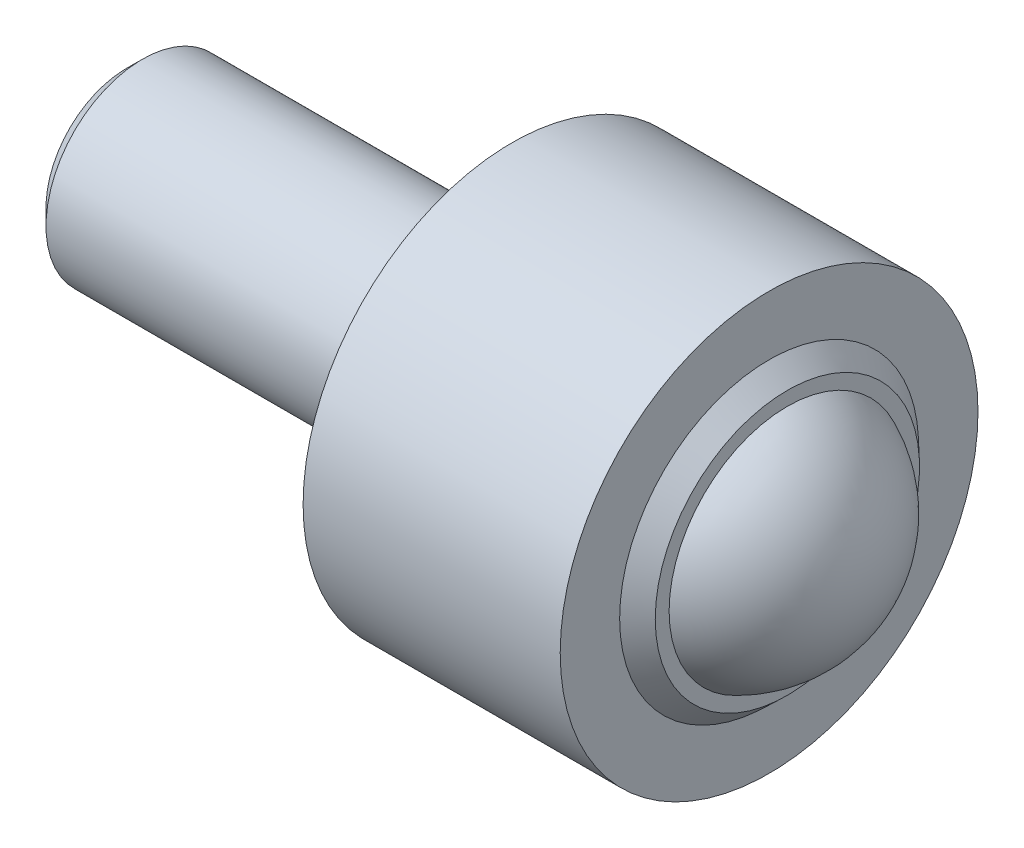
SolidWorks part; units mm, degrees
ref_plane "Front" through (0, 0, 0) normal (0, 0, 1) x (1, 0, 0)
ref_plane "Top" through (0, 0, 0) normal (0, 1, 0) x (1, 0, 0)
ref_plane "Right" through (0, 0, 0) normal (1, 0, 0) x (0, 0, -1)
sketch "草图1" plane through (0, 0, 0) normal (1, 0, 0) x (0, 0, -1)
  circle A0 centre (0, 0) radius 3
  dimension "D1" = 6
extrude "凸台-拉伸1" add sketch "草图1" along normal blind 12
cosmetic thread "装饰螺纹线1" parameters "D1"=5, "D2"=4.917
sketch "草图2" plane through (12, 0, 0) normal (1, 0, 0) x (0, 0, -1)
  circle A0 centre (0, 0) radius 6.5
  dimension "D1" = 13
extrude "凸台-拉伸2" add sketch "草图2" along normal blind 8
sketch "草图3" plane through (0, 0, 0) normal (0, 1, 0) x (1, 0, 0)
  line L0 (0, 0) -> (29.5776, 0) construction
  line L1 (20, -6.5) -> (20, 6.5) construction
  line L2 (15, 0) -> (23, 0)
  line L3 (20, 4.6509) -> (20.5681, 4.111)
  line L4 (20.5681, 4.111) -> (20.5681, 3.6798)
  line L5 (20, 4.6509) -> (20, 3.873)
  arc A0 (23, 0) -> (20.5681, 3.6798) centre (19, 0) ccw
  arc A1 (20, 3.873) -> (15, 0) centre (19, 0) ccw
  point P10 (21.1369, 3.3814)
  point P13 (20, 4.6509)
  point P14 (20.5681, 4.111)
  dimension "D1" = 8
  dimension "D2" = 1
revolve "旋转2" add sketch "草图3" angle 360 about L2
chamfer "倒角1" distance 0.5 angle 45 1 edges at (0, 0, -3)
